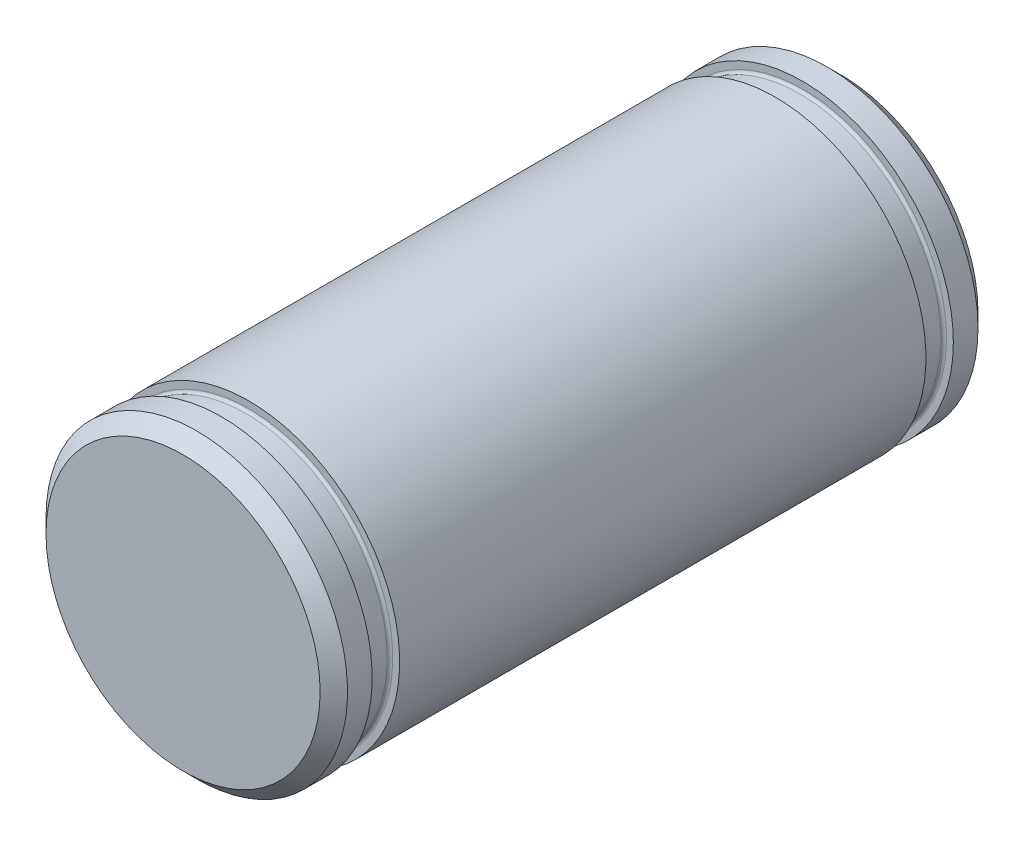
SolidWorks part; units mm, degrees
ref_plane "Plan de face" through (0, 0, 0) normal (0, 0, 1) x (1, 0, 0)
ref_plane "Plan de dessus" through (0, 0, 0) normal (0, 1, 0) x (1, 0, 0)
ref_plane "Plan de droite" through (0, 0, 0) normal (1, 0, 0) x (0, 0, -1)
sketch "Esquisse1" plane through (0, 0, 0) normal (0, 0, 1) x (1, 0, 0)
  circle A0 centre (0, 0) radius 5.5
  dimension "D1" = 11
extrude "Extrusion1" add sketch "Esquisse1" along normal mid plane 24
chamfer "Chanfrein1" distance 0.5 angle 45 1 edges at (5.5, 0, 12)
chamfer "Chanfrein2" distance 0.5 angle 45 1 edges at (5.5, 0, -12)
ref_plane "Plan1" through (0, 0, 24) normal (-1, 0, 0) x (0, 1, 0)
sketch "Esquisse3" plane through (0, 0, 24) normal (-1, 0, 0) x (0, 1, 0)
  line L0 (5.25, 13.4) -> (6.6, 13.4)
  line L1 (6.6, 13.4) -> (6.6, 14.4)
  line L2 (6.6, 14.4) -> (5.25, 14.4)
  line L3 (5.15, 14.3) -> (5.15, 13.5)
  line L4 (0, -50) -> (0, 50) construction
  arc A0 (5.15, 13.5) -> (5.25, 13.4) centre (5.25, 13.5) ccw
  arc A1 (5.15, 14.3) -> (5.25, 14.4) centre (5.25, 14.3) cw
  dimension "D1" = 0.1
  dimension "D2" = 0.1
  dimension "D3" = 9.6
revolve "Gorge pour ANSI B27.8M - 3DM1-11, Circlip haut rendement1" cut sketch "Esquisse3"
mirror "Symétrie1" about plane through (0, 0, 0) normal (0, 0, 1) of "Gorge pour ANSI B27.8M - 3DM1-11, Circlip haut rendement1"
